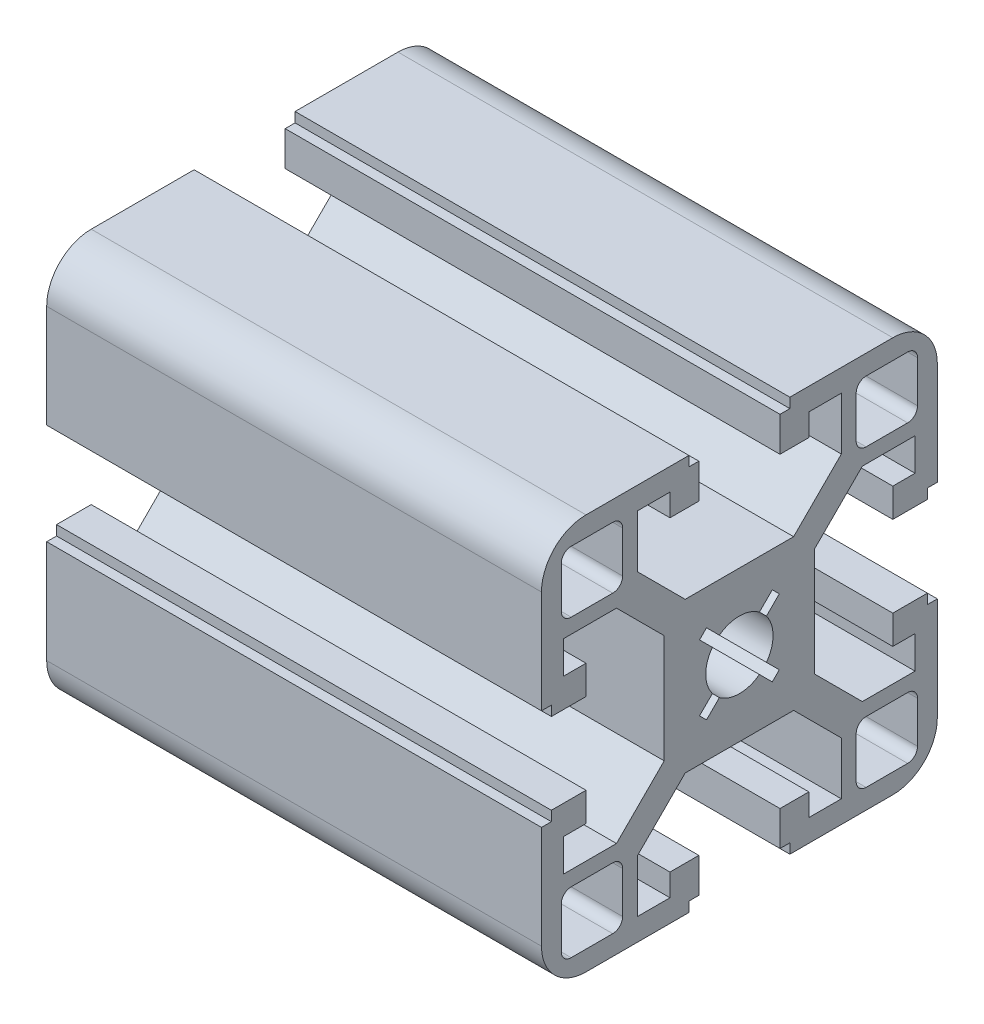
SolidWorks part; units mm, degrees
ref_plane "前视基准面" through (0, 0, 0) normal (0, 0, 1) x (1, 0, 0)
ref_plane "上视基准面" through (0, 0, 0) normal (0, 1, 0) x (1, 0, 0)
ref_plane "右视基准面" through (0, 0, 0) normal (1, 0, 0) x (0, 0, -1)
other "Configuration Table"
sketch "草图1" plane through (0, 0, 0) normal (1, 0, 0) x (0, 0, -1)
  line L0 (4.82, 19.28) -> (3.82, 19.28)
  line L1 (3.82, 19.28) -> (3.82, 15.78)
  line L2 (3.82, 15.78) -> (6.7364, 15.78)
  line L3 (6.7364, 15.78) -> (6.7364, 18.03)
  line L4 (6.7364, 18.03) -> (10.02, 18.03)
  line L5 (10.02, 18.03) -> (10.02, 12.7013)
  line L6 (10.02, 12.7013) -> (5.1987, 7.88)
  line L7 (5.1987, 7.88) -> (-5.7586, 7.88)
  line L8 (-5.7586, 7.88) -> (-10.58, 12.7013)
  line L9 (-10.58, 12.7013) -> (-10.58, 18.03)
  line L10 (-10.58, 18.03) -> (-7.2963, 18.03)
  line L11 (-7.2963, 18.03) -> (-7.2963, 15.78)
  line L12 (-7.2963, 15.78) -> (-4.38, 15.78)
  line L13 (-4.38, 15.78) -> (-4.38, 19.28)
  line L14 (-4.38, 19.28) -> (-5.38, 19.28)
  line L15 (-5.38, 19.28) -> (-5.38, 20.28)
  line L16 (-5.38, 20.28) -> (-15.78, 20.28)
  line L17 (-20.28, 15.78) -> (-20.28, 5.38)
  line L18 (-20.28, 5.38) -> (-19.28, 5.38)
  line L19 (-19.28, 5.38) -> (-19.28, 4.38)
  line L20 (-19.28, 4.38) -> (-15.78, 4.38)
  line L21 (-15.78, 4.38) -> (-15.78, 7.2963)
  line L22 (-15.78, 7.2963) -> (-18.03, 7.2963)
  line L23 (-18.03, 7.2963) -> (-18.03, 10.58)
  line L24 (-18.03, 10.58) -> (-12.7013, 10.58)
  line L25 (-12.7013, 10.58) -> (-7.88, 5.7586)
  line L26 (-7.88, 5.7586) -> (-7.88, -5.1987)
  line L27 (-7.88, -5.1987) -> (-12.7013, -10.02)
  line L28 (-12.7013, -10.02) -> (-18.03, -10.02)
  line L29 (-18.03, -10.02) -> (-18.03, -6.7364)
  line L30 (-18.03, -6.7364) -> (-15.78, -6.7364)
  line L31 (-15.78, -6.7364) -> (-15.78, -3.82)
  line L32 (-15.78, -3.82) -> (-19.28, -3.82)
  line L33 (-19.28, -3.82) -> (-19.28, -4.82)
  line L34 (-19.28, -4.82) -> (-20.28, -4.82)
  line L35 (-20.28, -4.82) -> (-20.28, -15.22)
  line L36 (-15.78, -19.72) -> (-5.38, -19.72)
  line L37 (-5.38, -19.72) -> (-5.38, -18.72)
  line L38 (-5.38, -18.72) -> (-4.38, -18.72)
  line L39 (-4.38, -18.72) -> (-4.38, -15.22)
  line L40 (-4.38, -15.22) -> (-7.2963, -15.22)
  line L41 (-7.2963, -15.22) -> (-7.2963, -17.47)
  line L42 (-7.2963, -17.47) -> (-10.58, -17.47)
  line L43 (-10.58, -17.47) -> (-10.58, -12.1414)
  line L44 (-10.58, -12.1414) -> (-5.7586, -7.32)
  line L45 (-5.7586, -7.32) -> (5.1987, -7.32)
  line L46 (5.1987, -7.32) -> (10.02, -12.1414)
  line L47 (10.02, -12.1414) -> (10.02, -17.47)
  line L48 (10.02, -17.47) -> (6.7364, -17.47)
  line L49 (6.7364, -17.47) -> (6.7364, -15.22)
  line L50 (6.7364, -15.22) -> (3.82, -15.22)
  line L51 (3.82, -15.22) -> (3.82, -18.72)
  line L52 (3.82, -18.72) -> (4.82, -18.72)
  line L53 (4.82, -18.72) -> (4.82, -19.72)
  line L54 (4.82, -19.72) -> (15.22, -19.72)
  line L55 (19.72, -15.22) -> (19.72, -4.82)
  line L56 (19.72, -4.82) -> (18.72, -4.82)
  line L57 (18.72, -4.82) -> (18.72, -3.82)
  line L58 (18.72, -3.82) -> (15.22, -3.82)
  line L59 (15.22, -3.82) -> (15.22, -6.7364)
  line L60 (15.22, -6.7364) -> (17.47, -6.7364)
  line L61 (17.47, -6.7364) -> (17.47, -10.02)
  line L62 (17.47, -10.02) -> (12.1414, -10.02)
  line L63 (12.1414, -10.02) -> (7.32, -5.1987)
  line L64 (7.32, -5.1987) -> (7.32, 5.7586)
  line L65 (7.32, 5.7586) -> (12.1414, 10.58)
  line L66 (12.1414, 10.58) -> (17.47, 10.58)
  line L67 (17.47, 10.58) -> (17.47, 7.2963)
  line L68 (17.47, 7.2963) -> (15.22, 7.2963)
  line L69 (15.22, 7.2963) -> (15.22, 4.38)
  line L70 (15.22, 4.38) -> (18.72, 4.38)
  line L71 (18.72, 4.38) -> (18.72, 5.38)
  line L72 (18.72, 5.38) -> (19.72, 5.38)
  line L73 (19.72, 5.38) -> (19.72, 15.78)
  line L74 (15.22, 20.28) -> (4.82, 20.28)
  line L75 (4.82, 20.28) -> (4.82, 19.28)
  line L76 (-13.08, -17.72) -> (-17.28, -17.72)
  line L77 (-18.28, -16.72) -> (-18.28, -12.52)
  line L78 (-17.28, -11.52) -> (-13.08, -11.52)
  line L79 (-12.08, -12.52) -> (-12.08, -16.72)
  line L80 (-17.28, 18.28) -> (-13.08, 18.28)
  line L81 (-12.08, 17.28) -> (-12.08, 13.08)
  line L82 (-13.08, 12.08) -> (-17.28, 12.08)
  line L83 (-18.28, 13.08) -> (-18.28, 17.28)
  line L84 (16.72, 12.08) -> (12.52, 12.08)
  line L85 (11.52, 13.08) -> (11.52, 17.28)
  line L86 (12.52, 18.28) -> (16.72, 18.28)
  line L87 (17.72, 17.28) -> (17.72, 13.08)
  line L88 (3.7505, -3.0434) -> (3.0434, -3.7505)
  line L89 (3.0434, -3.7505) -> (1.7445, -2.4516)
  line L90 (-2.3044, -2.4516) -> (-3.6033, -3.7505)
  line L91 (-3.6033, -3.7505) -> (-4.3104, -3.0434)
  line L92 (-4.3104, -3.0434) -> (-3.0115, -1.7445)
  line L93 (-3.0115, 2.3044) -> (-4.3104, 3.6033)
  line L94 (-4.3104, 3.6033) -> (-3.6033, 4.3104)
  line L95 (-3.6033, 4.3104) -> (-2.3044, 3.0115)
  line L96 (1.7445, 3.0115) -> (3.0434, 4.3104)
  line L97 (3.0434, 4.3104) -> (3.7505, 3.6033)
  line L98 (3.7505, 3.6033) -> (2.4516, 2.3044)
  line L99 (2.4516, -1.7445) -> (3.7505, -3.0434)
  line L100 (17.72, -12.52) -> (17.72, -16.72)
  line L101 (16.72, -17.72) -> (12.52, -17.72)
  line L102 (11.52, -16.72) -> (11.52, -12.52)
  line L103 (12.52, -11.52) -> (16.72, -11.52)
  arc A0 (-15.78, 20.28) -> (-20.28, 15.78) centre (-15.78, 15.78) ccw
  arc A1 (-20.28, -15.22) -> (-15.78, -19.72) centre (-15.78, -15.22) ccw
  arc A2 (15.22, -19.72) -> (19.72, -15.22) centre (15.22, -15.22) ccw
  arc A3 (19.72, 15.78) -> (15.22, 20.28) centre (15.22, 15.78) ccw
  arc A4 (-12.08, -16.72) -> (-13.08, -17.72) centre (-13.08, -16.72) cw
  arc A5 (-17.28, -17.72) -> (-18.28, -16.72) centre (-17.28, -16.72) cw
  arc A6 (-18.28, -12.52) -> (-17.28, -11.52) centre (-17.28, -12.52) cw
  arc A7 (-13.08, -11.52) -> (-12.08, -12.52) centre (-13.08, -12.52) cw
  arc A8 (-18.28, 17.28) -> (-17.28, 18.28) centre (-17.28, 17.28) cw
  arc A9 (-13.08, 18.28) -> (-12.08, 17.28) centre (-13.08, 17.28) cw
  arc A10 (-12.08, 13.08) -> (-13.08, 12.08) centre (-13.08, 13.08) cw
  arc A11 (-17.28, 12.08) -> (-18.28, 13.08) centre (-17.28, 13.08) cw
  arc A12 (17.72, 13.08) -> (16.72, 12.08) centre (16.72, 13.08) cw
  arc A13 (12.52, 12.08) -> (11.52, 13.08) centre (12.52, 13.08) cw
  arc A14 (11.52, 17.28) -> (12.52, 18.28) centre (12.52, 17.28) cw
  arc A15 (16.72, 18.28) -> (17.72, 17.28) centre (16.72, 17.28) cw
  arc A16 (1.7445, -2.4516) -> (-2.3044, -2.4516) centre (-0.28, 0.28) cw
  arc A17 (-3.0115, -1.7445) -> (-3.0115, 2.3044) centre (-0.28, 0.28) cw
  arc A18 (-2.3044, 3.0115) -> (1.7445, 3.0115) centre (-0.28, 0.28) cw
  arc A19 (2.4516, 2.3044) -> (2.4516, -1.7445) centre (-0.28, 0.28) cw
  arc A20 (16.72, -11.52) -> (17.72, -12.52) centre (16.72, -12.52) cw
  arc A21 (17.72, -16.72) -> (16.72, -17.72) centre (16.72, -16.72) cw
  arc A22 (12.52, -17.72) -> (11.52, -16.72) centre (12.52, -16.72) cw
  arc A23 (11.52, -12.52) -> (12.52, -11.52) centre (12.52, -12.52) cw
extrude "凸台-拉伸1" add sketch "草图1" against normal blind 50
